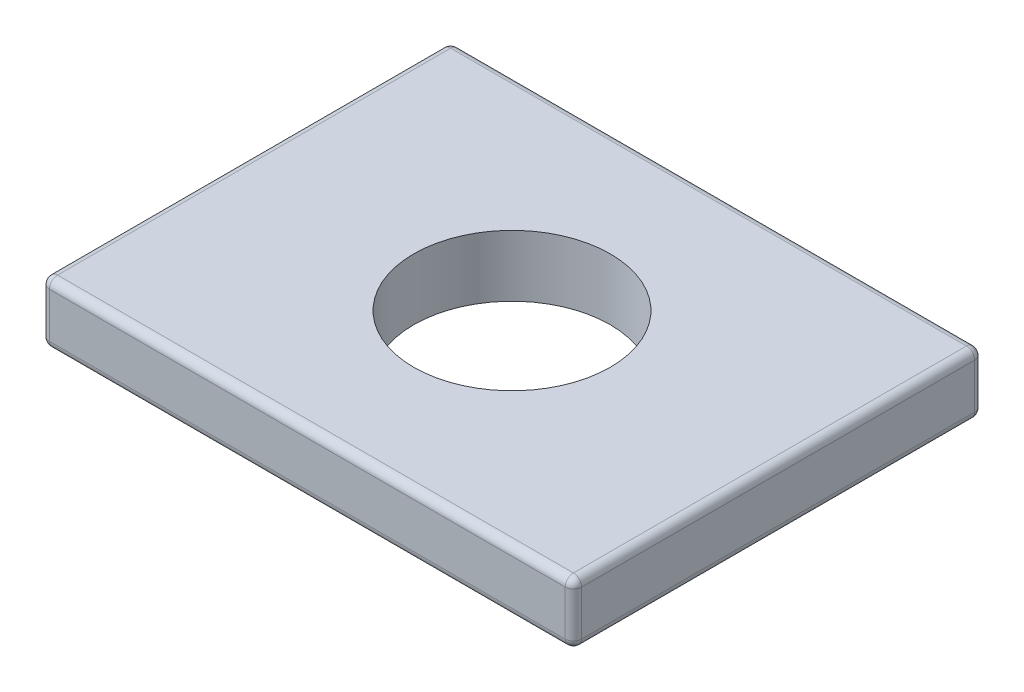
SolidWorks part; units mm, degrees
material "Windform LX 3.0"
ref_plane "Front Plane" through (0, 0, 0) normal (0, 0, 1) x (1, 0, 0)
ref_plane "Top Plane" through (0, 0, 0) normal (0, 1, 0) x (1, 0, 0)
ref_plane "Right Plane" through (0, 0, 0) normal (1, 0, 0) x (0, 0, -1)
sketch "Sketch1" plane through (0, 0, 0) normal (0, 1, 0) x (1, 0, 0)
  line L0 (0, 2.5) -> (0, -2.5) construction
  line L1 (-3.25, 2.5) -> (3.25, 2.5)
  line L2 (-3.25, 2.5) -> (-3.25, -2.5)
  line L3 (-3.25, -2.5) -> (3.25, -2.5)
  line L4 (3.25, 2.5) -> (3.25, -2.5)
  line L5 (-3.25, 0) -> (3.25, 0) construction
  point P8 (0, 0)
  dimension "D1" = 6.5
  dimension "D2" = 5
extrude "Boss-Extrude1" add sketch "Sketch1" along normal blind 0.75
hole_wizard "M2 Clearance Hole1" positions "Sketch2" profile "Sketch3" hole size "M2" standard "ISO"
sketch "Sketch2" plane through (0, 0.75, 0) normal (0, 1, 0) x (1, 0, 0)
  line L0 (3.25, -2.5) -> (3.25, 2.5) construction
  point P0 (0, 0)
  dimension "D1" = 3.25
sketch "Sketch3" plane through (0, 0.75, 0) normal (1, 0, 0) x (0, 0, 1)
  line L0 (0, 0) -> (0, 2.321)
  line L1 (0, 2.321) -> (1.2, 1.6)
  line L2 (1.2, 1.6) -> (1.2, 0)
  line L5 (1.2, 0) -> (0, 0)
  line L10 (0, 2.321) -> (-1.2, 1.6) construction
  line L11 (0, -6.35) -> (0, 107.95) construction
  dimension "Hole Dia." = 2.4
  dimension "Hole Depth" = 1.6
  dimension "Drill Angle" = 118
fillet "Fillet1" radius 0.1 12 edges at (3.25, 0.375, -2.5) (-3.25, 0.375, -2.5) (-3.25, 0.375, 2.5) (3.25, 0.375, 2.5) (0, 0, 2.5) (3.25, 0, 0) (0, 0, -2.5) (-3.25, 0, 0) (0, 0.75, -2.5) (3.25, 0.75, 0) (0, 0.75, 2.5) (-3.25, 0.75, 0)
